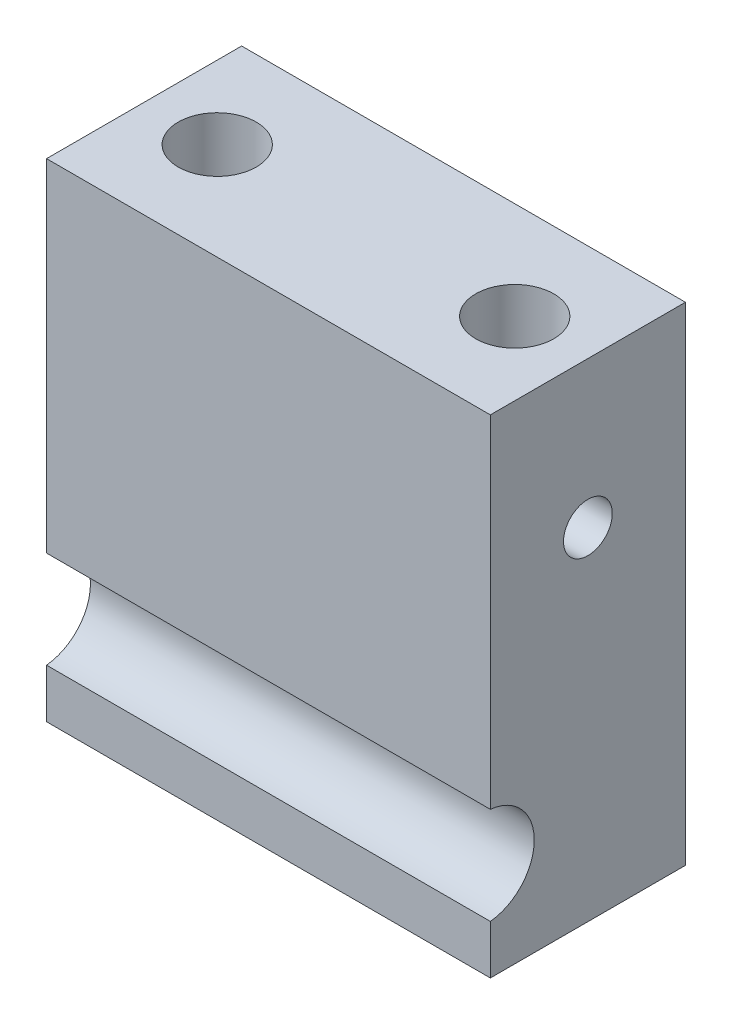
SolidWorks part; units mm, degrees
ref_plane "前视基准面" through (0, 0, 0) normal (0, 0, 1) x (1, 0, 0)
ref_plane "上视基准面" through (0, 0, 0) normal (0, 1, 0) x (1, 0, 0)
ref_plane "右视基准面" through (0, 0, 0) normal (1, 0, 0) x (0, 0, -1)
sketch "草图1" plane through (0, 0, 0) normal (0, 1, 0) x (1, 0, 0)
  line L1 (-4.55, 2) -> (4.55, 2)
  line L2 (-4.55, 2) -> (-4.55, -2)
  line L3 (-4.55, -2) -> (4.55, -2)
  line L4 (4.55, 2) -> (4.55, -2)
  line L5 (-4.55, 2) -> (4.55, -2) construction
  line L6 (-4.55, -2) -> (4.55, 2) construction
  point P0 (0, 0)
  dimension "D1" = 9.1
  dimension "D2" = 4
extrude "凸台-拉伸1" add sketch "草图1" along normal blind 10
sketch "草图2" plane through (-4.55, 0, 0) normal (-1, 0, 0) x (0, 0, 1)
  line L0 (-2, 10) -> (2, 10) construction
  line L1 (-2, 10) -> (-2, 0) construction
  circle A0 centre (0, 7) radius 0.5
  circle A1 centre (2.1, 2) radius 1
  dimension "D1" = 1
  dimension "D4" = 2
  dimension "D6" = 2.1
  dimension "D2" = 3
  dimension "D3" = 2
  dimension "D5" = 5
extrude "切除-拉伸1" cut sketch "草图2" against normal through all
sketch "草图3" plane through (0, 10, 0) normal (0, 1, 0) x (1, 0, 0)
  line L0 (4.55, 2) -> (-4.55, 2) construction
  line L1 (-4.55, 2) -> (-4.55, -2) construction
  line L2 (4.55, -2) -> (4.55, 2) construction
  circle A0 centre (3.05, 0) radius 0.8
  circle A1 centre (-3.05, 0) radius 0.8
  dimension "D1" = 1.6
  dimension "D2" = 1.6
  dimension "D6" = 1.5
  dimension "D3" = 2
  dimension "D4" = 2
  dimension "D5" = 1.5
extrude "切除-拉伸2" cut sketch "草图3" against normal blind 2
